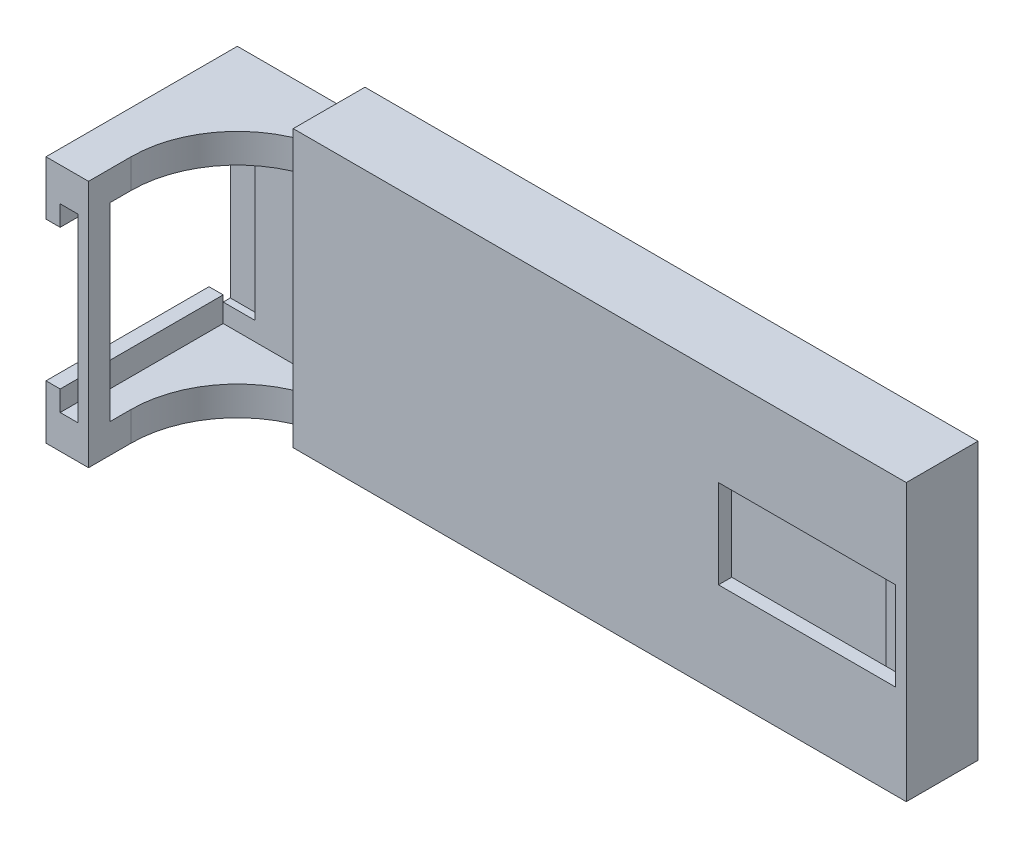
SolidWorks part; units mm, degrees
other "PCB Mount"
other "light shade cover"
ref_plane "Front Plane" through (0, 0, 0) normal (0, 0, 1) x (1, 0, 0)
ref_plane "Top Plane" through (0, 0, 0) normal (0, 1, 0) x (1, 0, 0)
ref_plane "Right Plane" through (0, 0, 0) normal (1, 0, 0) x (0, 0, -1)
sketch "Sketch1" plane through (0, 0, 0) normal (0, 0, 1) x (1, 0, 0)
  line L1 (0, 0) -> (85, 0)
  line L2 (0, 0) -> (0, 35)
  line L3 (0, 35) -> (85, 35)
  line L4 (85, 0) -> (85, 35)
  dimension "D1" = 85
  dimension "D2" = 35
extrude "Boss-Extrude1" add sketch "Sketch1" along normal blind 2
sketch "Sketch2" plane through (0, 0, 2) normal (0, 0, 1) x (1, 0, 0)
  line L0 (85, 0) -> (85, 35) construction
  line L1 (0, 2.125) -> (83, 2.125)
  line L2 (0, 2.125) -> (0, 32.875)
  line L3 (0, 32.875) -> (83, 32.875)
  line L4 (83, 2.125) -> (83, 32.875)
  line L5 (0, 35) -> (0, 0) construction
  line L7 (0, 35) -> (85, 35)
  line L8 (0, 35) -> (0, 0)
  line L9 (0, 0) -> (85, 0)
  line L10 (85, 35) -> (85, 0)
  point P6 (85, 17.5)
  point P7 (83, 17.5)
  line M5 (0, 35) -> (0, 0)
  line M6 (0, 0) -> (85, 0)
  line M7 (85, 0) -> (85, 35)
  line M8 (85, 35) -> (0, 35)
  dimension "D1" = 30.75
  dimension "D2" = 2
extrude "Boss-Extrude2" add sketch "Sketch2" along normal blind 2 contours L4 L1 L3 M5 M6 M7 M8
sketch "Sketch3" plane through (0, 0, 4) normal (0, 0, 1) x (1, 0, 0)
  line L0 (0, 32.875) -> (83, 32.875) construction
  line L1 (0, 0) -> (85, 0)
  line L2 (0, 0) -> (0, 35)
  line L3 (0, 35) -> (85, 35)
  line L4 (85, 0) -> (85, 35)
  line L5 (0, 30.875) -> (81.5, 30.875)
  line L6 (0, 30.875) -> (0, 4.125)
  line L7 (0, 4.125) -> (81.5, 4.125)
  line L8 (81.5, 30.875) -> (81.5, 4.125)
  line L9 (0, 2.125) -> (83, 2.125) construction
  line L11 (83, 2.125) -> (83, 32.875) construction
  line L13 (0, 0) -> (85, 0)
  line L14 (0, 0) -> (0, 35)
  line L15 (0, 35) -> (85, 35)
  line L16 (85, 0) -> (85, 35)
  line M9 (83, 32.875) -> (83, 2.125)
  line M10 (83, 2.125) -> (0, 2.125)
  line M11 (0, 2.125) -> (0, 0)
  line M12 (0, 0) -> (85, 0)
  line M13 (85, 0) -> (85, 35)
  line M14 (85, 35) -> (0, 35)
  line M15 (0, 35) -> (0, 32.875)
  line M16 (0, 32.875) -> (83, 32.875)
  dimension "D1" = 1.5
  dimension "D2" = 2
  dimension "D3" = 2
extrude "Boss-Extrude3" add sketch "Sketch3" along normal blind 2 contours L5 L8 L7 L2 M10 M9 M16 | M16 M9 M10 M11 M12 M13 M14 M15
sketch "Sketch5" plane through (85, 0, 0) normal (1, 0, 0) x (0, 0, -1)
  line L0 (0, 0) -> (0, 35) construction
  line L1 (2, 37) -> (-8.118, 37)
  line L2 (2, 37) -> (2, -2)
  line L3 (2, -2) -> (-8.118, -2)
  line L4 (-8.118, 37) -> (-8.118, -2)
  line L5 (-6, 35) -> (0, 35) construction
  line L6 (-6.25, 23.75) -> (-8.118, 23.75)
  line L7 (-6.25, 35.25) -> (0.25, 35.25)
  line L8 (-6.25, 35.25) -> (-6.25, -0.25)
  line L9 (-6.25, -0.25) -> (0.25, -0.25)
  line L10 (0.25, 35.25) -> (0.25, -0.25)
  line L11 (-6.25, 11.25) -> (-8.118, 11.25)
  point P12 (0, 17.5)
  point P13 (0.25, 17.5)
  point P14 (-3, 35)
  point P15 (-3, 35.25)
  point P20 (2, 17.5)
  dimension "D1" = 2
  dimension "D2" = 2
  dimension "D3" = 0.25
  dimension "D4" = 0.25
  dimension "D5" = 11.5
  dimension "D6" = 11.5
extrude "Boss-Extrude4" add sketch "Sketch5" against normal up to surface (85 mm away) separate body contours L8 L11 L4 L3 L2 L1 L6 L7 L10 L9 up to face at (0, 17.5, 3.6667)
sketch "Sketch6" plane through (85, 0, 0) normal (1, 0, 0) x (0, 0, -1)
  line L1 (-8.118, 37) -> (2, 37)
  line L2 (-8.118, 37) -> (-8.118, -2)
  line L3 (-8.118, -2) -> (2, -2)
  line L4 (2, 37) -> (2, -2)
extrude "Boss-Extrude5" add sketch "Sketch6" along normal blind 1.5
sketch "Sketch7" plane through (0, 0, 0) normal (-1, 0, 0) x (0, 0, 1)
  line L0 (6, 0) -> (0, 0) construction
  line L1 (0, 35) -> (6, 35)
  line L2 (0, 35) -> (0, 0)
  line L3 (0, 0) -> (6, 0)
  line L4 (6, 35) -> (6, 30.875)
  line L5 (4, 4.125) -> (4, 2.125)
  line L6 (2, 32.875) -> (4, 32.875)
  line L7 (2, 32.875) -> (2, 2.125)
  line L8 (2, 2.125) -> (4, 2.125)
  line L9 (4, 32.875) -> (4, 30.875)
  line L10 (4, 4.125) -> (6, 4.125)
  line L12 (4, 30.875) -> (6, 30.875)
  line L14 (6, 4.125) -> (6, 0)
extrude "Boss-Extrude6" add sketch "Sketch7" along normal blind 10
sketch "Sketch8" plane through (-10, 0, 0) normal (-1, 0, 0) x (0, 0, 1)
  line L0 (0, 0) -> (6, 0) construction
  line L1 (0, 35) -> (27, 35)
  line L2 (0, 35) -> (0, 0)
  line L3 (0, 0) -> (27, 0)
  line L4 (27, 35) -> (27, 0)
  line L6 (2, 32.875) -> (4, 32.875)
  line L7 (2, 32.875) -> (2, 2.125)
  line L8 (2, 2.125) -> (4, 2.125)
  line L9 (4, 32.875) -> (4, 2.125)
  line L10 (6, 30.875) -> (4, 30.875)
  line L11 (6, 30.875) -> (6, 4.125)
  line L12 (6, 4.125) -> (4, 4.125)
  line L13 (4, 30.875) -> (4, 4.125)
  line L14 (6, 30.875) -> (27, 30.875)
  line L15 (6, 30.875) -> (6, 4.125)
  line L16 (6, 4.125) -> (27, 4.125)
  line L17 (27, 30.875) -> (27, 4.125)
  line L18 (27, 35) -> (24, 35)
  line L19 (27, 35) -> (27, 0)
  line L20 (27, 0) -> (24, 0)
  line L21 (24, 35) -> (24, 0)
  line M5 (0, 35) -> (0, 0)
  line M6 (0, 0) -> (6, 0)
  line M7 (6, 0) -> (6, 4.125)
  line M8 (6, 4.125) -> (4, 4.125)
  line M9 (4, 4.125) -> (4, 2.125)
  line M10 (4, 2.125) -> (2, 2.125)
  line M11 (2, 2.125) -> (2, 32.875)
  line M12 (2, 32.875) -> (4, 32.875)
  line M13 (4, 32.875) -> (4, 30.875)
  line M14 (4, 30.875) -> (6, 30.875)
  line M15 (6, 30.875) -> (6, 35)
  line M16 (6, 35) -> (0, 35)
  dimension "D1" = 27
  dimension "D2" = 3
extrude "Boss-Extrude7" add sketch "Sketch8" along normal blind 1.5 contours M16 M5 M6 M7 M8 M9 M10 M11 M12 M13 M14 M15 | L21 L1 L14 M15 | L21 L16 L3 M7 | L16 L21 L3 L4 | L14 L21 L16 L4 | L1 L21 L14 L4
sketch "Sketch9" plane through (-11.5, 0, 0) normal (-1, 0, 0) x (0, 0, 1)
  line L0 (27, 35) -> (27, 0) construction
  line L1 (27, 30.25) -> (1, 30.25)
  line L2 (27, 30.25) -> (27, 4.75)
  line L3 (27, 4.75) -> (1, 4.75)
  line L4 (1, 30.25) -> (1, 4.75)
  line L6 (0, 35) -> (27, 35)
  line L7 (0, 35) -> (0, 0)
  line L8 (0, 0) -> (27, 0)
  line L9 (27, 35) -> (27, 0)
  line L10 (2, 32.875) -> (4, 32.875)
  line L11 (2, 32.875) -> (2, 2.125)
  line L12 (2, 2.125) -> (4, 2.125)
  line L13 (4, 32.875) -> (4, 2.125)
  line L14 (4, 4.125) -> (6, 4.125)
  line L15 (4, 4.125) -> (4, 30.875)
  line L16 (4, 30.875) -> (6, 30.875)
  line L17 (6, 4.125) -> (6, 30.875)
  point P6 (27, 17.5)
  point P7 (27, 17.5)
  line M5 (0, 0) -> (27, 0)
  line M6 (27, 0) -> (27, 35)
  line M7 (27, 35) -> (0, 35)
  line M8 (0, 35) -> (0, 0)
  line M9 (24, 30.875) -> (24, 4.125)
  line M10 (24, 4.125) -> (4, 4.125)
  line M11 (4, 4.125) -> (4, 2.125)
  line M12 (4, 2.125) -> (2, 2.125)
  line M13 (2, 2.125) -> (2, 32.875)
  line M14 (2, 32.875) -> (4, 32.875)
  line M15 (4, 32.875) -> (4, 30.875)
  line M16 (4, 30.875) -> (24, 30.875)
  dimension "D1" = 25.5
  dimension "D2" = 26
extrude "Boss-Extrude8" add sketch "Sketch9" along normal blind 2.5 contours L4 L1 L3 M13 M14 M15 M16 M9 M6 M7 M8 M5 M10 M11 M12
sketch "Sketch10" plane through (-14, 0, 0) normal (-1, 0, 0) x (0, 0, 1)
  line L0 (4, 32.875) -> (4, 30.875) construction
  line L1 (0, 35) -> (27, 35)
  line L2 (0, 35) -> (0, 0)
  line L3 (0, 0) -> (27, 0)
  line L4 (27, 35) -> (27, 0)
  line L5 (27, 35) -> (4, 35)
  line L6 (27, 35) -> (27, 27.375)
  line L7 (27, 27.375) -> (4, 27.375)
  line L8 (4, 35) -> (4, 27.375)
  line L9 (27, 0) -> (4, 0)
  line L10 (27, 0) -> (27, 7.625)
  line L11 (27, 7.625) -> (4, 7.625)
  line L12 (4, 0) -> (4, 7.625)
  line L13 (4, 30.875) -> (24, 30.875) construction
  line L15 (0, 35) -> (4, 35)
  line L16 (0, 35) -> (0, 0)
  line L17 (0, 0) -> (4, 0)
  line L18 (4, 35) -> (4, 0)
  line L19 (2, 32.875) -> (4, 32.875)
  line L20 (2, 32.875) -> (2, 2.125)
  line L21 (2, 2.125) -> (4, 2.125)
  line L22 (4, 32.875) -> (4, 2.125)
  line L23 (1, 4.75) -> (2, 4.75)
  line L24 (1, 4.75) -> (1, 30.25)
  line L25 (1, 30.25) -> (2, 30.25)
  line L26 (2, 4.75) -> (2, 30.25)
  line M17 (1, 4.75) -> (1, 30.25)
  line M18 (1, 30.25) -> (2, 30.25)
  line M19 (2, 30.25) -> (2, 32.875)
  line M20 (2, 32.875) -> (4, 32.875)
  line M21 (4, 32.875) -> (4, 30.875)
  line M22 (4, 30.875) -> (24, 30.875)
  line M23 (24, 30.875) -> (24, 30.25)
  line M24 (24, 30.25) -> (27, 30.25)
  line M25 (27, 30.25) -> (27, 35)
  line M26 (27, 35) -> (0, 35)
  line M27 (0, 35) -> (0, 0)
  line M28 (0, 0) -> (27, 0)
  line M29 (27, 0) -> (27, 4.75)
  line M30 (27, 4.75) -> (24, 4.75)
  line M31 (24, 4.75) -> (24, 4.125)
  line M32 (24, 4.125) -> (4, 4.125)
  line M33 (4, 4.125) -> (4, 2.125)
  line M34 (4, 2.125) -> (2, 2.125)
  line M35 (2, 2.125) -> (2, 4.75)
  line M36 (2, 4.75) -> (1, 4.75)
  dimension "D1" = 3.5
extrude "Boss-Extrude9" add sketch "Sketch10" along normal blind 2 contours L8 M26 M21 M22 M23 M24 M25 | L8 L7 L4 M22 M24 M23 | L12 L8 L1 M28 M34 M35 M36 M17 M18 M19 M20 M27 | L12 L3 M29 M30 M31 M32 M33 | L12 L4 L11 M32 M31 M30
fillet "Fillet2" radius 15 2 edges at (-10, 2.0625, 6) (-10, 32.9375, 6)
sketch "Sketch11" plane through (0, 0, 8.118) normal (0, 0, 1) x (1, 0, 0)
  line L0 (0, -2) -> (86.5, -2) construction
  line L1 (0, 37) -> (60, 37)
  line L2 (0, 37) -> (0, -2)
  line L3 (0, -2) -> (60, -2)
  line L4 (60, 37) -> (60, -2)
  dimension "D1" = 60
extrude "Boss-Extrude10" add sketch "Sketch11" against normal up to surface (1.868 mm away) up to face at (42.5, 29.5, 6.25)
